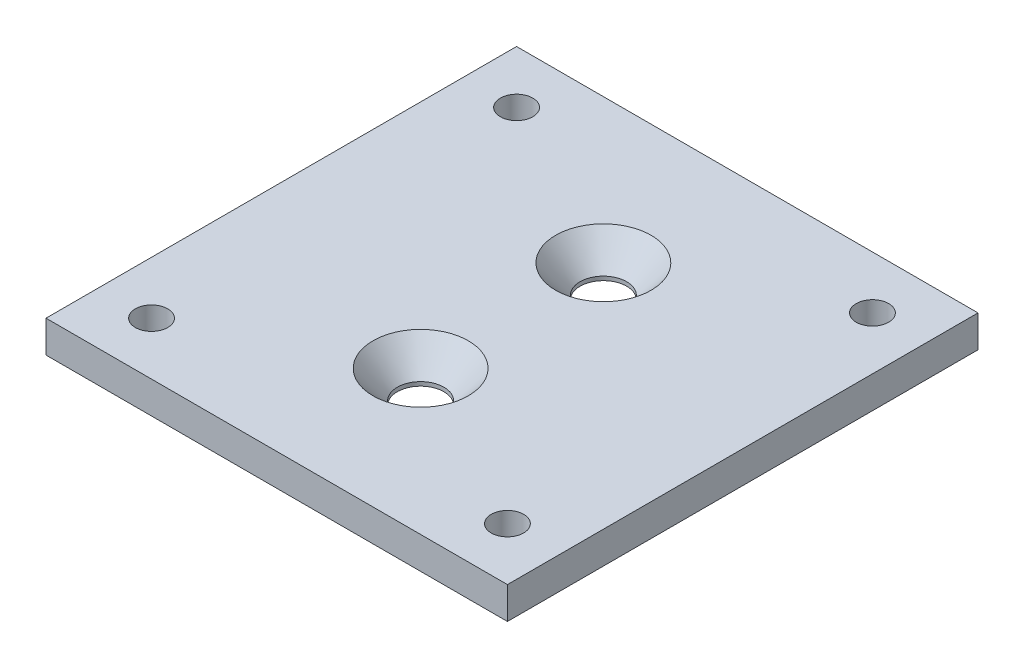
SolidWorks part; units mm, degrees
ref_plane "Front Plane" through (0, 0, 0) normal (0, 0, 1) x (1, 0, 0)
ref_plane "Top Plane" through (0, 0, 0) normal (0, 1, 0) x (1, 0, 0)
ref_plane "Right Plane" through (0, 0, 0) normal (1, 0, 0) x (0, 0, -1)
sketch "Sketch1" plane through (0, 0, 0) normal (0, 1, 0) x (1, 0, 0)
  line L1 (-19.475, -19.975) -> (19.475, -19.975)
  line L2 (-19.475, -19.975) -> (-19.475, 19.975)
  line L3 (-19.475, 19.975) -> (19.475, 19.975)
  line L4 (19.475, -19.975) -> (19.475, 19.975)
  line L5 (-19.475, -19.975) -> (19.475, 19.975) construction
  line L6 (-19.475, 19.975) -> (19.475, -19.975) construction
  line L7 (-25.25, -25.75) -> (25.25, -25.75)
  line L8 (-25.25, -25.75) -> (-25.25, 25.75)
  line L9 (-25.25, 25.75) -> (25.25, 25.75)
  line L10 (25.25, -25.75) -> (25.25, 25.75)
  line L11 (-25.25, -25.75) -> (25.25, 25.75) construction
  line L12 (-25.25, 25.75) -> (25.25, -25.75) construction
  circle A0 centre (-19.475, 19.975) radius 1.775
  circle A1 centre (19.475, 19.975) radius 1.775
  circle A2 centre (19.475, -19.975) radius 1.775
  circle A3 centre (-19.475, -19.975) radius 1.775
  point P0 (0, 0)
  point P10 (0, 0)
  dimension "D1" = 3.55
  dimension "D2" = 43.5
  dimension "D3" = 42.5
  dimension "D4" = 35.4
  dimension "D5" = 36.4
  dimension "D6" = 4
  dimension "D7" = 4
extrude "Boss-Extrude1" add sketch "Sketch1" along normal blind 3.5 contours L7 L10 L9 L8 A3 L2 A0 L3 A1 L4 A2 L1 | A3 L1 A2 L4 A1 L3 A0 L2
sketch "Sketch2" plane through (0, 3.5, 0) normal (0, 1, 0) x (1, 0, 0)
  line L0 (0, 10) -> (0, -10)
  circle A0 centre (0, 10) radius 3
  circle A1 centre (0, -10) radius 3
  point P4 (0, 0)
  dimension "D1" = 6
  dimension "D2" = 6
hole_wizard "CSK for #10 Flat Head Socket Cap Screw1" positions "Sketch3" profile "Sketch4" countersink size "#10" standard "ANSI Inch" end condition through all
sketch "Sketch3" plane through (0, 3.5, 0) normal (0, 1, 0) x (1, 0, 0)
  point P0 (0, 10)
  point P3 (0, -10)
sketch "Sketch4" plane through (0, 3.5, -10) normal (1, 0, 0) x (0, 0, 1)
  line L0 (0, 0) -> (0, 3.5)
  line L1 (0, 3.5) -> (2.5527, 3.5)
  line L2 (2.5527, 3.5) -> (2.5527, 3.068)
  line L3 (2.5527, 3.068) -> (5.2197, 0)
  line L5 (5.2197, 0) -> (0, 0)
  line L6 (-2.5527, 3.068) -> (-5.2197, 0) construction
  line L11 (0, -6.35) -> (0, 107.95) construction
  dimension "Thru Hole Dia." = 5.1054
  dimension "Thru Hole Depth" = 3.5
  dimension "Near C'Sink Dia." = 10.4394
  dimension "Near C'Sink Angle" = 82
ref_plane "Plane1" through (0, 0, -4.25) normal (0, 0, 1) x (1, 0, 0)
split "Split1" [suppressed] bodies to split 102
